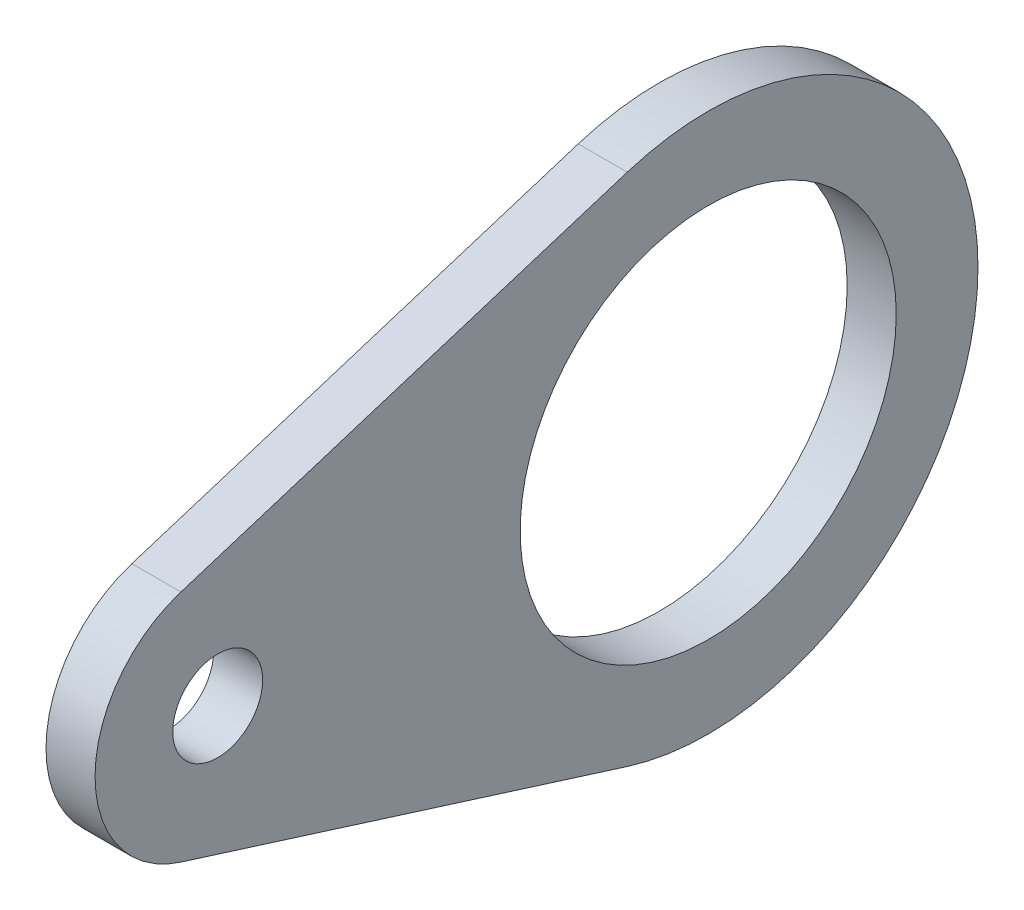
SolidWorks part; units mm, degrees
material "Q235"
ref_plane "前视基准面" through (0, 0, 0) normal (0, 0, 1) x (1, 0, 0)
ref_plane "上视基准面" through (0, 0, 0) normal (0, 1, 0) x (1, 0, 0)
ref_plane "右视基准面" through (0, 0, 0) normal (1, 0, 0) x (0, 0, -1)
sketch "草图1" plane through (0, 0, 0) normal (1, 0, 0) x (0, 0, -1)
  line L0 (0, 0) -> (-60, 0) construction
  line L1 (-64.5, 14.3091) -> (-9.9, 31.48)
  line L2 (-64.5, -14.3091) -> (-9.9, -31.48)
  circle A0 centre (0, 0) radius 23
  circle A1 centre (-60, 0) radius 5.5
  arc A2 (-64.5, 14.3091) -> (-64.5, -14.3091) centre (-60, 0) ccw
  arc A3 (-9.9, -31.48) -> (-9.9, 31.48) centre (0, 0) ccw
  dimension "D1" = 46
  dimension "D3" = 11
  dimension "D4" = 30
  dimension "D5" = 66
  dimension "D2" = 60
extrude "凸台-拉伸1" add sketch "草图1" along normal blind 6
